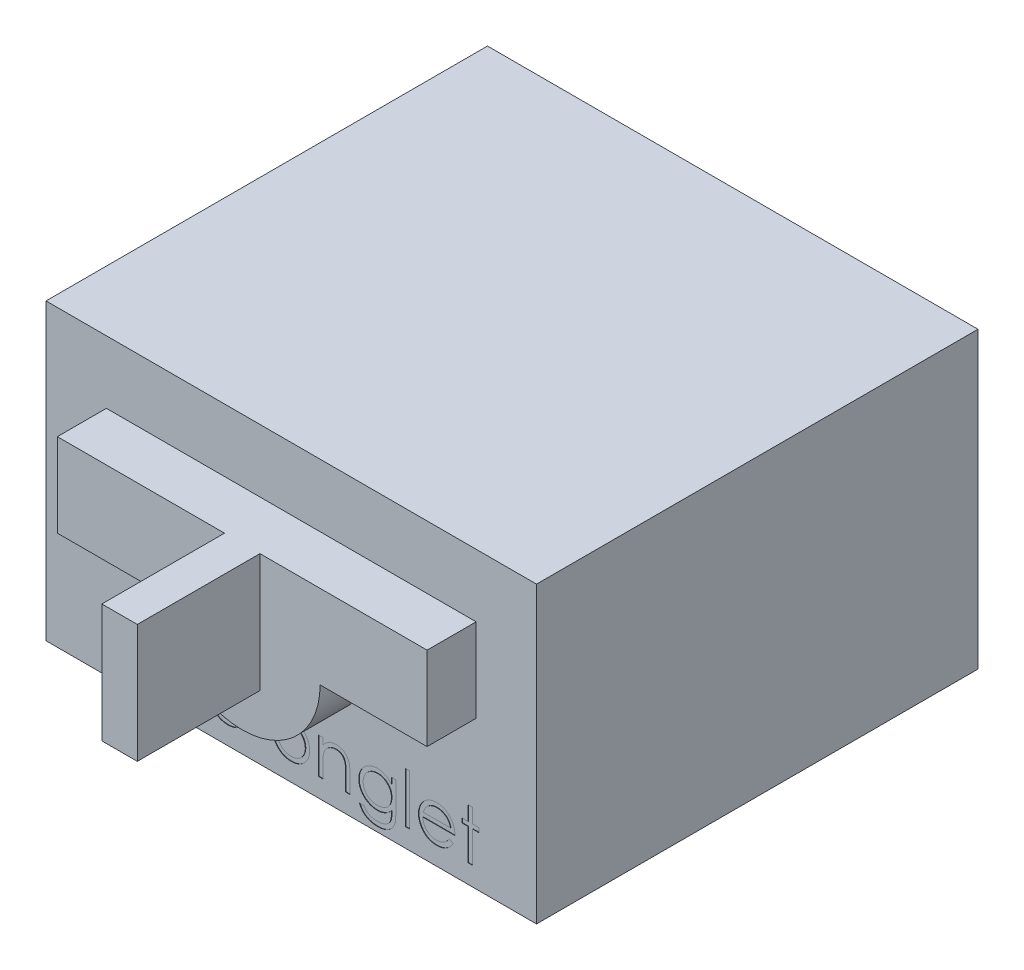
SolidWorks part; units mm, degrees
ref_plane "Front" through (0, 0, 0) normal (0, 0, 1) x (1, 0, 0)
ref_plane "Top" through (0, 0, 0) normal (0, 1, 0) x (1, 0, 0)
ref_plane "Right" through (0, 0, 0) normal (1, 0, 0) x (0, 0, -1)
sketch "Esquisse1" plane through (0, 0, 0) normal (0, 0, 1) x (1, 0, 0)
  line L1 (0, 0) -> (1000, 0)
  line L2 (0, 0) -> (0, 600)
  line L3 (0, 600) -> (1000, 600)
  line L4 (1000, 0) -> (1000, 600)
  dimension "D1" = 1000
  dimension "D2" = 600
extrude "Boss.-Extru.1" add sketch "Esquisse1" along normal blind 900
sketch "Esquisse2" plane through (0, 0, 900) normal (0, 0, 1) x (1, 0, 0)
  line L0 (123.1347, 471.9157) -> (123.1347, 301.5488)
  line L1 (123.1347, 301.5488) -> (341.1326, 301.5488)
  line L2 (341.1326, 301.5488) -> (658.8674, 301.5488) construction
  line L3 (500, 301.5488) -> (500, 142.6813) construction
  line L4 (500, 301.5488) -> (500, 600) construction
  line L5 (1000, 600) -> (0, 600) construction
  line L6 (123.1347, 471.9157) -> (876.8653, 471.9157)
  line L7 (876.8653, 301.5488) -> (658.8674, 301.5488)
  line L8 (876.8653, 471.9157) -> (876.8653, 301.5488)
  arc A0 (341.1326, 301.5488) -> (658.8674, 301.5488) centre (500, 301.5488) ccw
  point P13 (500, 471.9157)
extrude "Boss.-Extru.2" add sketch "Esquisse2" along normal blind 100
sketch "Esquisse3" plane through (0, 0, 1000) normal (0, 0, 1) x (1, 0, 0)
  line L0 (876.8653, 471.9157) -> (123.1347, 471.9157) construction
  line L1 (463.8622, 471.9157) -> (536.1378, 471.9157)
  line L2 (463.8622, 471.9157) -> (463.8622, 230.1271)
  line L3 (463.8622, 230.1271) -> (536.1378, 230.1271)
  line L4 (536.1378, 471.9157) -> (536.1378, 230.1271)
  line L5 (500, 230.1271) -> (500, 471.9157) construction
extrude "Boss.-Extru.3" add sketch "Esquisse3" along normal blind 250
sketch "Esquisse4" plane through (0, 0, 900) normal (0, 0, 1) x (1, 0, 0)
  text T0 "Scie onglet" font "Century Gothic" height 100
extrude "Enlèv. mat.-Extru.1" cut sketch "Esquisse4" against normal blind 1
